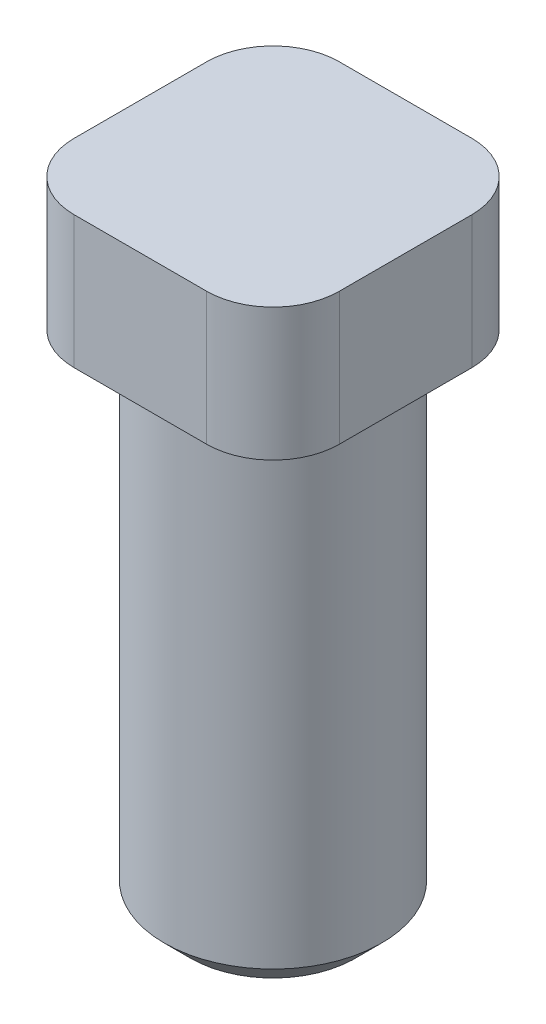
SolidWorks part; units mm, degrees
ref_plane "Front Plane" through (0, 0, 0) normal (0, 0, 1) x (1, 0, 0)
ref_plane "Top Plane" through (0, 0, 0) normal (0, 1, 0) x (1, 0, 0)
ref_plane "Right Plane" through (0, 0, 0) normal (1, 0, 0) x (0, 0, -1)
sketch "Sketch1" plane through (0, 0, 0) normal (0, 1, 0) x (1, 0, 0)
  circle A0 centre (0, 0) radius 4.1
  dimension "D1" = 8.2
extrude "Boss-Extrude1" add sketch "Sketch1" along normal blind 19
sketch "Sketch2" plane through (0, 19, 0) normal (0, 1, 0) x (1, 0, 0)
  line L0 (-4.1, 0) -> (0, 0) construction
  line L1 (-5, 5) -> (5, 5) construction
  line L2 (-5, -5) -> (5, -5) construction
  line L3 (0, 0) -> (4.1, 0) construction
  line L9 (-7.1342, -5) -> (7.1342, 5) construction
  line L10 (-7.1342, 5) -> (7.1342, -5) construction
  line L11 (-5, -5) -> (5, -5)
  line L12 (-5, -5) -> (-5, 5)
  line L13 (-5, 5) -> (5, 5)
  line L14 (5, -5) -> (5, 5)
  line L15 (-5, -5) -> (5, 5) construction
  line L16 (-5, 5) -> (5, -5) construction
  arc A0 (5, -5) -> (5, 5) centre (5, 0) ccw construction
  arc A1 (-5, 5) -> (-5, -5) centre (-5, 0) ccw construction
  circle A2 centre (0, 0) radius 4.1 construction
  arc A3 (0, 0) -> (-5, 5) centre (-5, 0) ccw construction
  arc A4 (-5, -5) -> (0, 0) centre (-5, 0) ccw construction
  arc A5 (5, 5) -> (0, 0) centre (5, 0) ccw construction
  arc A6 (0, 0) -> (5, -5) centre (5, 0) ccw construction
  dimension "D1" = 10
  dimension "D2" = 5
  dimension "D3" = 5
  dimension "D4" = 10
  dimension "D5" = 14.2684
  dimension "D6" = 10
  dimension "D7" = 10
extrude "Boss-Extrude2" add sketch "Sketch2" along normal blind 5
fillet "Fillet1" radius 2.5 4 edges at (-5, 21.5, -5) (5, 21.5, -5) (5, 21.5, 5) (-5, 21.5, 5)
chamfer "Chamfer1" distance 1 angle 45 1 edges at (0, 0, 4.1)
